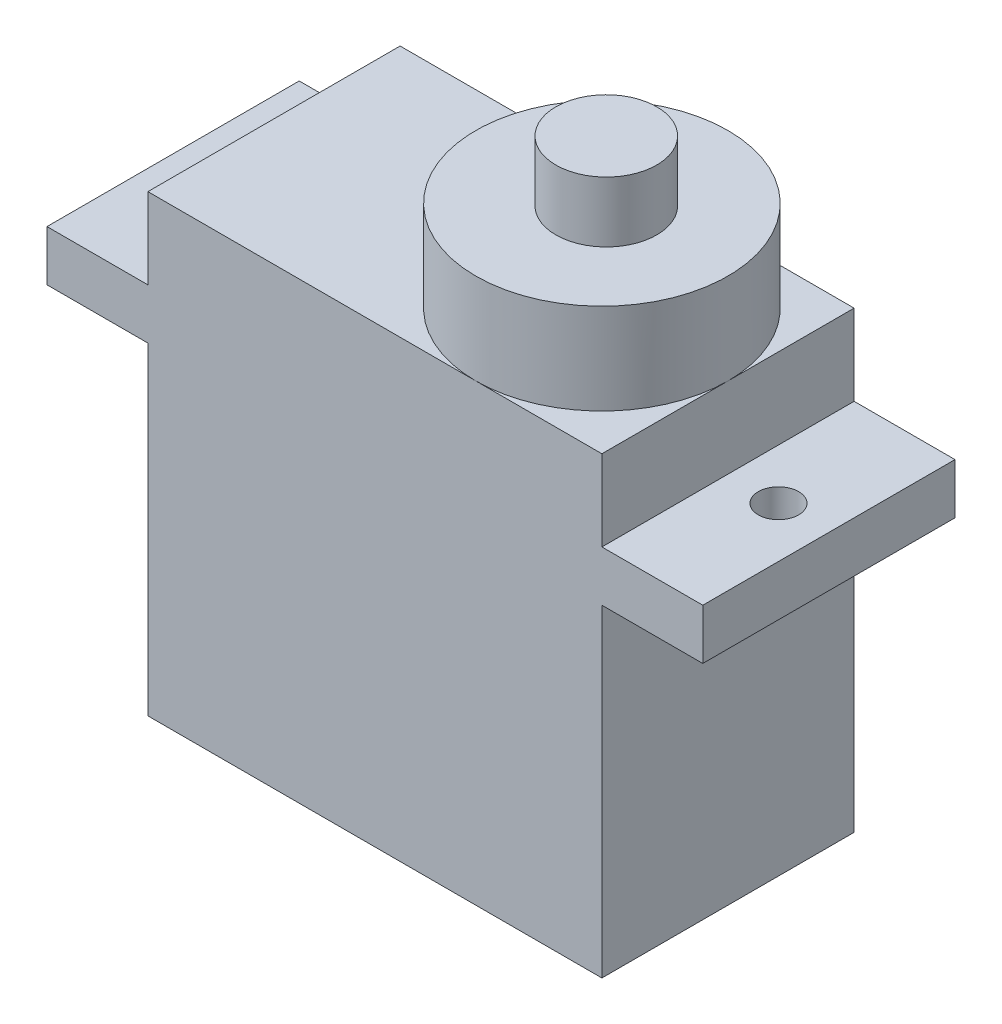
SolidWorks part; units mm, degrees
ref_plane "Alzado" through (0, 0, 0) normal (0, 0, 1) x (1, 0, 0)
ref_plane "Planta" through (0, 0, 0) normal (0, 1, 0) x (1, 0, 0)
ref_plane "Vista lateral" through (0, 0, 0) normal (1, 0, 0) x (0, 0, -1)
sketch "Croquis1" plane through (0, 0, 0) normal (0, 1, 0) x (1, 0, 0)
  line L1 (-11.25, 6.25) -> (11.25, 6.25)
  line L2 (-11.25, 6.25) -> (-11.25, -6.25)
  line L3 (-11.25, -6.25) -> (11.25, -6.25)
  line L4 (11.25, 6.25) -> (11.25, -6.25)
  line L5 (-11.25, 6.25) -> (11.25, -6.25) construction
  line L6 (-11.25, -6.25) -> (11.25, 6.25) construction
  point P0 (0, 0)
  dimension "D1" = 12.5
  dimension "D2" = 22.5
extrude "Saliente-Extruir1" add sketch "Croquis1" along normal blind 22.5
sketch "Croquis2" plane through (0, 0, 6.25) normal (0, 0, 1) x (1, 0, 0)
  line L0 (11.25, 22.5) -> (11.25, 0) construction
  line L1 (11.25, 18.5) -> (16.25, 18.5)
  line L2 (11.25, 18.5) -> (11.25, 16)
  line L3 (11.25, 16) -> (16.25, 16)
  line L4 (16.25, 18.5) -> (16.25, 16)
  line L5 (-11.25, 22.5) -> (-11.25, 0) construction
  line L6 (-11.25, 18.5) -> (-16.25, 18.5)
  line L7 (-11.25, 18.5) -> (-11.25, 16)
  line L8 (-11.25, 16) -> (-16.25, 16)
  line L9 (-16.25, 18.5) -> (-16.25, 16)
  line L10 (-11.25, 22.5) -> (11.25, 22.5) construction
  dimension "D1" = 5
  dimension "D2" = 5
  dimension "D3" = 2.5
  dimension "D4" = 2.5
  dimension "D5" = 4
  dimension "D6" = 4
extrude "Saliente-Extruir2" add sketch "Croquis2" against normal blind 12.5
sketch "Croquis3" plane through (0, 18.5, 0) normal (0, 1, 0) x (1, 0, 0)
  line L0 (16.25, 6.25) -> (11.25, 6.25) construction
  line L1 (16.25, 6.25) -> (16.25, -6.25) construction
  line L2 (-11.25, 6.25) -> (-16.25, 6.25) construction
  line L4 (-16.25, 6.25) -> (-16.25, -6.25) construction
  circle A0 centre (13.75, 0) radius 1
  circle A1 centre (-13.75, 0) radius 1
  point P8 (0, 0)
  dimension "D1" = 2
  dimension "D2" = 2
  dimension "D3" = 6.25
  dimension "D4" = 2.5
  dimension "D5" = 6.25
  dimension "D6" = 2.5
extrude "Cortar-Extruir1" cut sketch "Croquis3" against normal up to next
sketch "Croquis4" plane through (0, 22.5, 0) normal (0, 1, 0) x (1, 0, 0)
  line L0 (11.25, 6.25) -> (11.25, -6.25) construction
  line L1 (11.25, 6.25) -> (-11.25, 6.25) construction
  circle A0 centre (5, 0) radius 6.25
  dimension "D3" = 12.5
  dimension "D1" = 6.25
  dimension "D2" = 6.25
extrude "Saliente-Extruir3" add sketch "Croquis4" along normal blind 4.5
sketch "Croquis5" plane through (0, 27, 0) normal (0, 1, 0) x (1, 0, 0)
  circle A0 centre (5.2184, 0) radius 2.5
  dimension "D1" = 5
extrude "Saliente-Extruir4" add sketch "Croquis5" along normal blind 3
